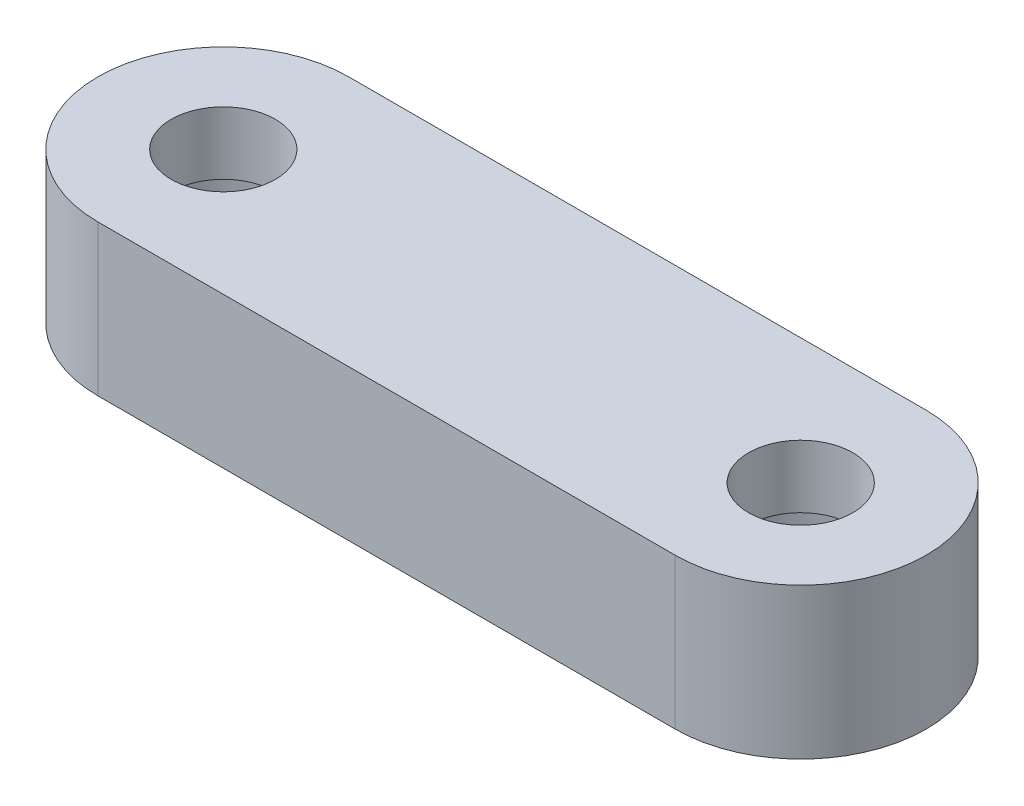
SolidWorks part; units mm, degrees
ref_plane "前视基准面" through (0, 0, 0) normal (0, 0, 1) x (1, 0, 0)
ref_plane "上视基准面" through (0, 0, 0) normal (0, 1, 0) x (1, 0, 0)
ref_plane "右视基准面" through (0, 0, 0) normal (1, 0, 0) x (0, 0, -1)
other "Configuration Table"
sketch "草图1" plane through (0, 0, 0) normal (0, 1, 0) x (1, 0, 0)
  line L0 (0, 0) -> (23, 0) construction
  line L1 (0, 5) -> (23, 5)
  line L2 (0, -5) -> (23, -5)
  arc A0 (0, 5) -> (0, -5) centre (0, 0) ccw
  arc A1 (23, -5) -> (23, 5) centre (23, 0) ccw
  point P3 (11.5, 0)
  dimension "D1" = 10
  dimension "D2" = 23
extrude "凸台-拉伸1" add sketch "草图1" along normal blind 6
sketch "草图2" plane through (0, 0, 0) normal (0, 0, 1) x (1, 0, 0)
  line L0 (0, 0) -> (0, 10.2724) construction
  line L1 (0, 0) -> (-3.75, 0)
  line L2 (-5, 0) -> (0, 0) construction
  line L3 (-3.75, 0) -> (-3.75, 3.5)
  line L4 (-3.75, 3.5) -> (-2.075, 3.5)
  line L5 (-2.075, 3.5) -> (-2.075, 6)
  line L6 (0, 6) -> (-5, 6) construction
  line L7 (-2.075, 6) -> (0, 6)
  line L8 (0, 0) -> (0, 6)
  dimension "D1" = 4.15
  dimension "D2" = 7.5
  dimension "D3" = 3.5
revolve "切除-旋转1" cut sketch "草图2" angle 360 about L0
sketch "草图3" plane through (0, 0, 0) normal (0, 0, 1) x (1, 0, 0)
  line L0 (23, 6) -> (23, 0) construction
  line L1 (23, 0) -> (19.25, 0)
  line L2 (0, 0) -> (23, 0) construction
  line L3 (19.25, 0) -> (19.25, 3.5)
  line L4 (19.25, 3.5) -> (20.925, 3.5)
  line L5 (20.925, 3.5) -> (20.925, 6)
  line L6 (0, 6) -> (23, 6) construction
  line L7 (20.925, 6) -> (23, 6)
  line L8 (23, 6) -> (23, 0)
  dimension "D1" = 4.15
  dimension "D2" = 7.5
  dimension "D3" = 3.5
revolve "切除-旋转2" cut sketch "草图3" angle 360 about L0
